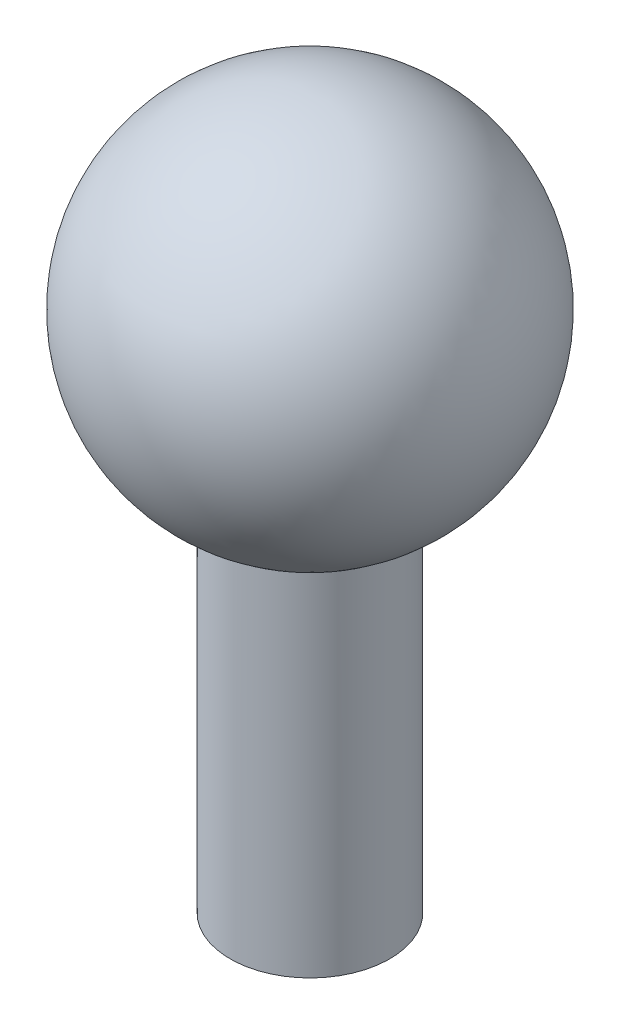
SolidWorks part; units mm, degrees
ref_plane "Płaszczyzna przednia" through (0, 0, 0) normal (0, 0, 1) x (1, 0, 0)
ref_plane "Płaszczyzna górna" through (0, 0, 0) normal (0, 1, 0) x (1, 0, 0)
ref_plane "Płaszczyzna prawa" through (0, 0, 0) normal (1, 0, 0) x (0, 0, -1)
sketch "Szkic1" plane through (0, 0, 0) normal (0, 0, 1) x (1, 0, 0)
  line L0 (-3, -6.3246) -> (-3, -19.6423)
  line L1 (-3, -19.6423) -> (0, -19.6423)
  line L2 (0, -19.6423) -> (0, 7)
  arc A0 (0, 7) -> (-3, -6.3246) centre (0, 0) ccw
  dimension "D1" = 14
  dimension "D2" = 13.3178
  dimension "D3" = 3
revolve "Obrót1" add sketch "Szkic1" angle 360 about L2
